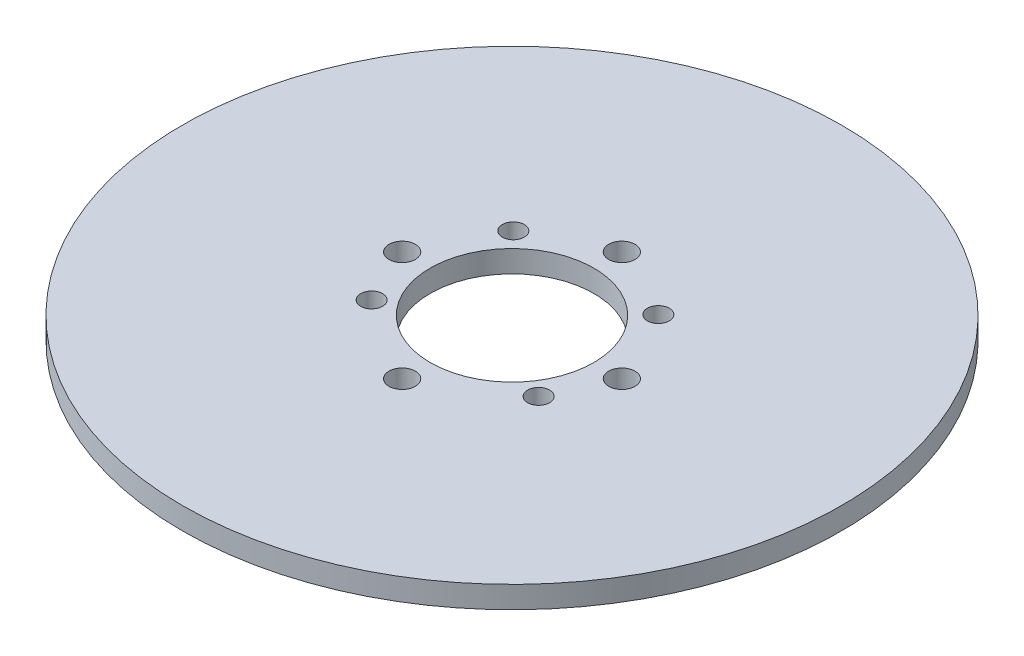
SolidWorks part; units mm, degrees
ref_plane "Front Plane" through (0, 0, 0) normal (0, 0, 1) x (1, 0, 0)
ref_plane "Top Plane" through (0, 0, 0) normal (0, 1, 0) x (1, 0, 0)
ref_plane "Right Plane" through (0, 0, 0) normal (1, 0, 0) x (0, 0, -1)
sketch "Sketch1" plane through (0, 0, 0) normal (0, 1, 0) x (1, 0, 0)
  line L0 (-33, 30.5941) -> (-38, -28.8961) construction
  line L1 (33, 30.5941) -> (38, -28.8961) construction
  line L2 (-33, 30.5941) -> (38, -28.8961) construction
  line L3 (33, 30.5941) -> (-38, -28.8961) construction
  line L4 (-33, 30.5941) -> (33, 30.5941) construction
  line L5 (-33, 30.5941) -> (0, 0) construction
  circle A0 centre (-33, 30.5941) radius 5
  circle A1 centre (33, 30.5941) radius 5
  circle A3 centre (38, -28.8961) radius 5
  circle A4 centre (-38, -28.8961) radius 5
  arc A10 (33.5486, 15.6042) -> (34.2563, 15.6468) centre (33, 30.5941) ccw
  circle A11 centre (0, -3) radius 37.25
  circle A12 centre (0, 47) radius 6
  circle A13 centre (50, -3) radius 6
  circle A14 centre (0, -53) radius 6
  circle A15 centre (-50, -3) radius 6
  circle A16 centre (0, -3) radius 150
  point P2 (0, 30.5941)
  point P25 (0, -3)
  dimension "D4" = 10
  dimension "D1" = 59.7
  dimension "D6" = 3
  dimension "D7" = 50
  dimension "D8" = 12
  dimension "D9" = 4
  dimension "D10" = 300
  dimension "D11" = 74.5
  dimension "D2" = 66
  dimension "D3" = 45
  dimension "D5" = 76
extrude "Boss-Extrude1" add sketch "Sketch1" along normal blind 10
